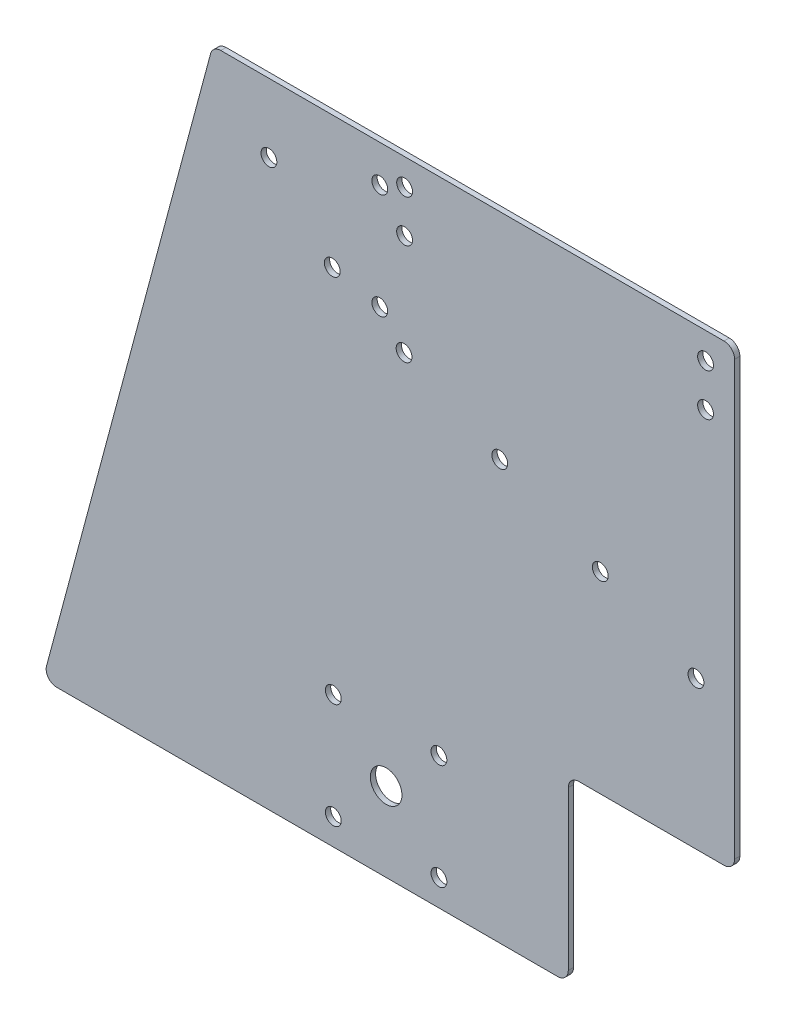
SolidWorks part; units mm, degrees
ref_plane "前视基准面" through (0, 0, 0) normal (0, 0, 1) x (1, 0, 0)
ref_plane "上视基准面" through (0, 0, 0) normal (0, 1, 0) x (1, 0, 0)
ref_plane "右视基准面" through (0, 0, 0) normal (1, 0, 0) x (0, 0, -1)
other "Configuration Table"
sketch "草图1" plane through (0, 0, 0) normal (0, 0, 1) x (1, 0, 0)
  line L0 (0, 0) -> (-145, 0)
  line L1 (-145, 0) -> (-112.8461, 120)
  line L2 (-112.8461, 120) -> (0, 120)
  line L3 (0, 120) -> (0, 0)
  line L5 (-90, 25) -> (-70, 25) construction
  line L6 (-90, 25) -> (-90, 5) construction
  line L7 (-90, 5) -> (-70, 5) construction
  line L8 (-70, 25) -> (-70, 5) construction
  line L9 (-90, 25) -> (-70, 5) construction
  line L10 (-90, 5) -> (-70, 25) construction
  circle A0 centre (-70, 25) radius 1.5
  circle A1 centre (-90, 25) radius 1.5
  circle A2 centre (-80, 15) radius 3
  circle A3 centre (-70, 5) radius 1.5
  circle A4 centre (-90, 5) radius 1.5
  point P5 (-80, 15)
  dimension "D2" = 3
  dimension "D8" = 6
  dimension "D1" = 20
  dimension "D3" = 15
  dimension "D4" = 80
  dimension "D5" = 75
  dimension "D6" = 120
  dimension "D7" = 145
extrude "凸台-拉伸1" add sketch "草图1" along normal blind 1
sketch "草图2" plane through (0, 0, 1) normal (0, 0, 1) x (1, 0, 0)
  line L0 (0, 120) -> (-112.8461, 120) construction
  line L1 (0, 0) -> (46.5, 0)
  line L2 (0, 0) -> (0, 120)
  line L3 (0, 120) -> (46.5, 120)
  line L4 (46.5, 0) -> (46.5, 120)
  dimension "D1" = 46.5
extrude "凸台-拉伸2" add sketch "草图2" against normal blind 1
sketch "草图7" plane through (0, 0, 1) normal (0, 0, 1) x (1, 0, 0)
  line L0 (-90.2, 95) -> (-102.2, 107) construction
  line L1 (46.5, 120) -> (-112.8461, 120) construction
  line L2 (46.5, 0) -> (46.5, 120) construction
  circle A0 centre (-102.2, 107) radius 1.5
  circle A1 centre (-90.2, 95) radius 1.5
  dimension "D1" = 3
  dimension "D2" = 13
  dimension "D3" = 148.7
  dimension "D4" = 12
  dimension "D5" = 12
extrude "切除-拉伸5" cut sketch "草图7" against normal blind 10
sketch "草图6" [suppressed] plane through (0, 0, 1) normal (0, 0, 1) x (1, 0, 0)
  line L0 (26.5, 100) -> (26.5, 80) construction
  line L1 (26.5, 80) -> (26.5, 60) construction
  line L2 (26.5, 60) -> (26.5, 40) construction
  line L4 (46.5, 120) -> (-112.8461, 120) construction
  line L5 (46.5, 0) -> (46.5, 120) construction
  circle A0 centre (26.5, 100) radius 1.5
  circle A1 centre (26.5, 80) radius 1.5
  circle A2 centre (26.5, 60) radius 1.5
  circle A3 centre (26.5, 40) radius 1.5
  dimension "D5" = 3
  dimension "D4" = 20
  dimension "D1" = 20
  dimension "D2" = 20
  dimension "D3" = 20
  dimension "D6" = 20
extrude "切除-拉伸4" [suppressed] cut sketch "草图6" against normal blind 1
sketch "草图4" plane through (0, 0, 1) normal (0, 0, 1) x (1, 0, 0)
  line L0 (-112.8461, 120) -> (-145, 0) construction
  line L1 (-52.9914, 66.1716) -> (-21.1716, 97.9914) construction
  line L2 (-52.9914, 66.1716) -> (-39.9099, 53.0901) construction
  line L3 (-39.9099, 53.0901) -> (-8.0901, 84.9099) construction
  line L4 (-21.1716, 97.9914) -> (-8.0901, 84.9099) construction
  line L5 (-52.9914, 66.1716) -> (-8.0901, 84.9099) construction
  line L6 (-30.5407, 75.5407) -> (-30.5407, 53.0087) construction
  line L7 (-30.5407, 75.5407) -> (-125.497, 75.5407) construction
  line L8 (46.5, 120) -> (-112.8461, 120) construction
  line L9 (-24, 69) -> (-146.4628, 69) construction
  line L10 (-24, 69) -> (-24, -11.2692) construction
  circle A0 centre (-21.1716, 97.9914) radius 1.5
  circle A1 centre (-8.0901, 84.9099) radius 1.5
  circle A2 centre (-39.9099, 53.0901) radius 1.5
  circle A3 centre (-52.9914, 66.1716) radius 1.5
  dimension "D3" = 3
  dimension "D1" = 45
  dimension "D2" = 18.5
  dimension "D4" = 51
  dimension "D5" = 24
  dimension "D6" = 60
extrude "切除-拉伸2" [suppressed] cut sketch "草图4" against normal blind 1
sketch "草图5" [suppressed] plane through (0, 0, 1) normal (0, 0, 1) x (1, 0, 0)
  line L0 (-112.8461, 120) -> (-145, 0) construction
  line L5 (-39.9099, 53.0901) -> (-8.0901, 84.9099) construction
  line L6 (-39.9099, 53.0901) -> (-55.4663, 68.6464) construction
  line L7 (-55.4663, 68.6464) -> (-23.6464, 100.4663) construction
  line L8 (-8.0901, 84.9099) -> (-23.6464, 100.4663) construction
  line L9 (-39.9099, 53.0901) -> (-23.6464, 100.4663) construction
  line L10 (-55.4663, 68.6464) -> (-8.0901, 84.9099) construction
  line L12 (-24, 69) -> (-143.9156, 69) construction
  line L13 (-24, 69) -> (-24, -29.9571) construction
  line L14 (46.5, 120) -> (-112.8461, 120) construction
  circle A0 centre (-23.6464, 100.4663) radius 1.5
  circle A1 centre (-8.0901, 84.9099) radius 1.5
  circle A2 centre (-39.9099, 53.0901) radius 1.5
  circle A3 centre (-55.4663, 68.6464) radius 1.5
  point P0 (-31.7782, 76.7782)
  dimension "D4" = 3
  dimension "D1" = 24
  dimension "D2" = 45
  dimension "D3" = 22
  dimension "D5" = 51
  dimension "D6" = 60
extrude "切除-拉伸3" [suppressed] cut sketch "草图5" against normal blind 1
sketch "草图8" plane through (0, 0, 1) normal (0, 0, 1) x (1, 0, 0)
  line L0 (42.5, 103) -> (42.5, 83) construction
  line L1 (46.5, 0) -> (46.5, 120) construction
  line L2 (46.5, 120) -> (-112.8461, 120) construction
  circle A0 centre (42.5, 103) radius 1.5
  circle A1 centre (42.5, 83) radius 1.5
  dimension "D3" = 3
  dimension "D4" = 17
  dimension "D1" = 20
  dimension "D2" = 4
extrude "切除-拉伸6" cut sketch "草图8" against normal blind 10
sketch "草图10" plane through (0, 0, 1) normal (0, 0, 1) x (1, 0, 0)
  line L1 (46.5, 0) -> (-4.5, 0)
  line L2 (46.5, 0) -> (46.5, 30)
  line L3 (46.5, 30) -> (-4.5, 30)
  line L4 (-4.5, 0) -> (-4.5, 30)
  dimension "D1" = 30
  dimension "D2" = 51
extrude "切除-拉伸7" cut sketch "草图10" against normal blind 10
sketch "草图11" plane through (0, 0, 0) normal (0, 0, -1) x (-1, 0, 0)
  line L0 (-46.5, 47.6485) -> (-9.5, 47.6485) construction
  line L1 (-46.5, 30) -> (-46.5, 120) construction
  line L2 (-9.5, 47.6485) -> (21.3145, 62.0175) construction
  line L3 (21.3145, 62.0175) -> (58.4731, 79.3449) construction
  line L4 (58.4731, 79.3449) -> (76.5992, 87.7972) construction
  line L6 (-22.5, 46) -> (26.3814, 68.7937) construction
  line L7 (-22.5, 46) -> (-46.5, 46) construction
  line L8 (4.5, 30) -> (-46.5, 30) construction
  circle A0 centre (76.5992, 87.7972) radius 1.5
  circle A1 centre (58.4731, 79.3449) radius 1.5
  circle A2 centre (21.3145, 62.0175) radius 1.5
  circle A4 centre (39.4406, 70.4699) radius 1.5
  dimension "D5" = 3
  dimension "D6" = 20
  dimension "D9" = 21
  dimension "D10" = 20
  dimension "D1" = 24
  dimension "D2" = 16
  dimension "D3" = 34
  dimension "D4" = 155
  dimension "D7" = 4
  dimension "D8" = 37
extrude "切除-拉伸8" cut sketch "草图11" against normal blind 65
sketch "草图12" plane through (0, 0, 0) normal (0, 0, -1) x (-1, 0, 0)
  line L0 (84.2, 120) -> (84.2, 80) construction
  line L1 (-46.5, 120) -> (112.8461, 120) construction
  line L2 (81.2, 113) -> (81.2, 93) construction
  circle A0 centre (81.2, 113) radius 1.5
  circle A1 centre (81.2, 93) radius 1.5
  circle A2 centre (90.2, 95) radius 1.5 construction
  point P6 (84.2, 100)
  dimension "D5" = 3
  dimension "D1" = 40
  dimension "D2" = 3
  dimension "D3" = 7
  dimension "D4" = 20
  dimension "D6" = 6
extrude "切除-拉伸9" cut sketch "草图12" against normal blind 10
sketch "草图13" plane through (0, 0, 0) normal (0, 0, -1) x (-1, 0, 0)
  line L0 (4.5, 30) -> (-46.5, 30) construction
  line L1 (4.5, 0) -> (45.5, 0)
  line L2 (4.5, 0) -> (4.5, 30)
  line L3 (4.5, 30) -> (45.5, 30)
  line L4 (45.5, 0) -> (45.5, 30)
  dimension "D1" = 41
extrude "切除-拉伸10" cut sketch "草图13" against normal blind 10
sketch "草图14" plane through (0, 0, 0) normal (0, 0, -1) x (-1, 0, 0)
  line L0 (-46.5, 30) -> (-46.5, 120) construction
  line L1 (-46.5, 120) -> (112.8461, 120) construction
  circle A0 centre (-28.5, 104) radius 10
  dimension "D1" = 20
  dimension "D2" = 18
  dimension "D3" = 16
extrude "切除-拉伸11" cut sketch "草图14" against normal blind 10
sketch "草图16" plane through (0, 0, 0) normal (0, 0, -1) x (-1, 0, 0)
  line L0 (-46.5, 120) -> (112.8461, 120) construction
  line L1 (19.5, 115) -> (76.5, 115) construction
  line L2 (19.5, 115) -> (19.5, 107) construction
  line L3 (19.5, 107) -> (76.5, 107) construction
  line L4 (76.5, 115) -> (76.5, 107) construction
  line L5 (-46.5, 30) -> (-46.5, 120) construction
  circle A0 centre (76.5, 115) radius 1.5
  circle A1 centre (76.5, 107) radius 1.5
  circle A2 centre (19.5, 107) radius 1.5
  circle A3 centre (19.5, 115) radius 1.5
  dimension "D3" = 3
  dimension "D1" = 57
  dimension "D2" = 8
  dimension "D4" = 5
  dimension "D5" = 66
extrude "切除-拉伸13" cut sketch "草图16" against normal blind 1
sketch "草图17" plane through (0, 0, 0) normal (0, 0, -1) x (-1, 0, 0)
  line L0 (-34.5, 115) -> (-14.5, 115) construction
  line L1 (-46.5, 120) -> (112.8461, 120) construction
  line L2 (-46.5, 30) -> (-46.5, 120) construction
  circle A0 centre (-14.5, 115) radius 1.5
  circle A1 centre (-34.5, 115) radius 1.5
  dimension "D3" = 3
  dimension "D4" = 12
  dimension "D1" = 20
  dimension "D2" = 5
extrude "切除-拉伸14" cut sketch "草图17" against normal blind 10
sketch "草图18" plane through (0, 0, 0) normal (0, 0, -1) x (-1, 0, 0)
  line L0 (-46.5, 30) -> (-46.5, 120) construction
  line L1 (-46.5, 34) -> (45.5, 34)
  line L2 (-46.5, 34) -> (-46.5, 30)
  line L3 (-46.5, 30) -> (45.5, 30)
  line L4 (45.5, 34) -> (45.5, 30)
  line L5 (45.5, 30) -> (-46.5, 30) construction
  line L6 (45.5, 0) -> (45.5, 30) construction
  dimension "D1" = 4
extrude "切除-拉伸15" cut sketch "草图18" against normal blind 10
fillet "圆角2" radius 2 6 edges at (-45.5, 0, 0.5) (-145, 0, 0.5) (-112.8461, 120, 0.5) (46.5, 120, 0.5) (-45.5, 34, 0.5) (46.5, 34, 0.5)
sketch "草图19" plane through (0, 0, 0) normal (0, 0, -1) x (-1, 0, 0)
  circle A0 centre (-28.5, 104) radius 10 construction
  circle A1 centre (-28.5, 104) radius 10
extrude "凸台-拉伸3" add sketch "草图19" against normal blind 1
sketch "草图20" plane through (0, 0, 0) normal (0, 0, -1) x (-1, 0, 0)
  line L0 (-44.5, 120) -> (111.3114, 120) construction
  line L1 (14, 120) -> (-46.5, 120)
  line L2 (14, 120) -> (14, 34)
  line L3 (14, 34) -> (-46.5, 34)
  line L4 (-46.5, 120) -> (-46.5, 34)
  line L5 (43.5, 34) -> (-44.5, 34) construction
  line L6 (-46.5, 36) -> (-46.5, 118) construction
  dimension "D1" = 60.5
extrude "切除-拉伸16" cut sketch "草图20" against normal blind 10
fillet "圆角3" radius 2 2 edges at (-14, 34, 0.5) (-14, 120, 0.5)
